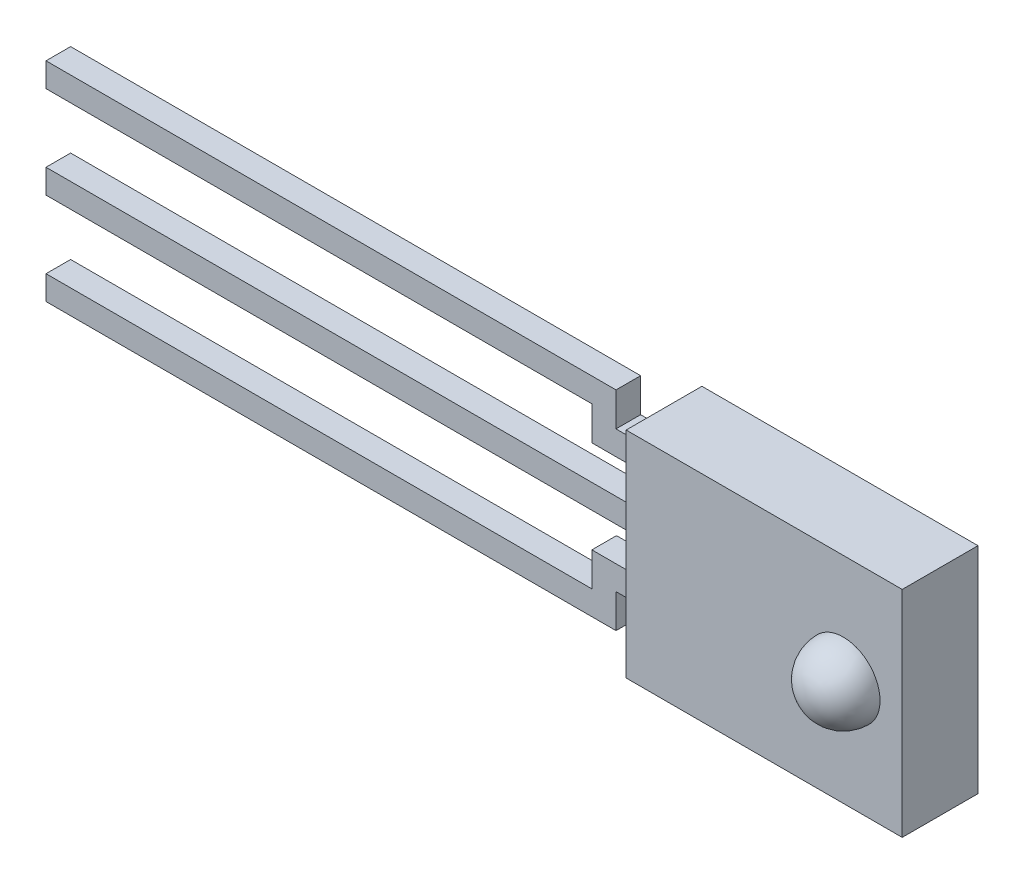
SolidWorks part; units mm, degrees
ref_plane "Plan de face" through (0, 0, 0) normal (0, 0, 1) x (1, 0, 0)
ref_plane "Plan de dessus" through (0, 0, 0) normal (0, 1, 0) x (1, 0, 0)
ref_plane "Plan de droite" through (0, 0, 0) normal (1, 0, 0) x (0, 0, -1)
sketch "Esquisse1" plane through (0, 0, 0) normal (0, 0, 1) x (1, 0, 0)
  line L1 (-4.5, 2.225) -> (1.22, 2.225)
  line L2 (-4.5, 2.225) -> (-4.5, -2.225)
  line L3 (-4.5, -2.225) -> (1.22, -2.225)
  line L4 (1.22, 2.225) -> (1.22, -2.225)
  line L5 (-4.5, 2.225) -> (1.22, -2.225) construction
  line L6 (-4.5, -2.225) -> (1.22, 2.225) construction
  point P0 (-1.64, 0)
  dimension "D1" = 4.45
  dimension "D2" = 5.72
  dimension "D3" = 1.22
extrude "Boss.-Extru.1" add sketch "Esquisse1" along normal blind 1.57
sketch "Esquisse2" plane through (0, 0, 0) normal (0, 1, 0) x (1, 0, 0)
  line L0 (1.22, -1.57) -> (-4.5, -1.57) construction
  line L1 (0, 0) -> (0, -2.7313) construction
  line L2 (0, -0.81) -> (0, -2.33)
  arc A0 (0, -2.33) -> (0, -0.81) centre (0, -1.57) ccw
  dimension "D1" = 1.52
revolve "Révolution5" add sketch "Esquisse2" angle 360 about L1
sketch "Esquisse3" plane through (0, 0, 1.57) normal (0, 0, 1) x (1, 0, 0)
  line L0 (-4.5, 1.46) -> (-5.39, 1.46)
  line L1 (-4.5, 2.225) -> (-4.5, -2.225) construction
  line L2 (-5.39, 1.46) -> (-5.39, 2.16)
  line L3 (-5.39, 2.16) -> (-17.2, 2.16)
  line L4 (-17.2, 2.16) -> (-17.2, 1.66)
  line L5 (-17.2, 1.66) -> (-5.89, 1.66)
  line L6 (-5.89, 1.66) -> (-5.89, 0.96)
  line L7 (-5.89, 0.96) -> (-4.5, 0.96)
  line L8 (-4.5, 0.96) -> (-4.5, 1.46)
  line L9 (-17.2, 1.91) -> (-6.2508, 1.91) construction
  line L10 (0, 0) -> (-8.6945, 0) construction
  dimension "D2" = 0.5
  dimension "D1" = 0.89
  dimension "D3" = 0.5
  dimension "D4" = 0.5
  dimension "D5" = 1.91
  dimension "D6" = 0.7
  dimension "D7" = 12.7
extrude "Boss.-Extru.2" add sketch "Esquisse3" against normal blind 0.51 from offset 0.68 offset against normal yes
mirror "Symétrie1" about plane through (0, 0, 0) normal (0, 1, 0) of "Boss.-Extru.2"
sketch "Esquisse4" plane through (0, 0, 0.89) normal (0, 0, 1) x (1, 0, 0)
  line L0 (-4.5, 2.225) -> (-4.5, -2.225) construction
  line L1 (-4.5, 0.25) -> (-17.2, 0.25)
  line L2 (-4.5, 0.25) -> (-4.5, -0.25)
  line L3 (-4.5, -0.25) -> (-17.2, -0.25)
  line L4 (-17.2, 0.25) -> (-17.2, -0.25)
  line L5 (-17.2, 2.16) -> (-17.2, 1.66) construction
  line L6 (0, 0) -> (-9.7531, 0) construction
  dimension "D1" = 0.5
extrude "Boss.-Extru.3" add sketch "Esquisse4" against normal blind 0.51
